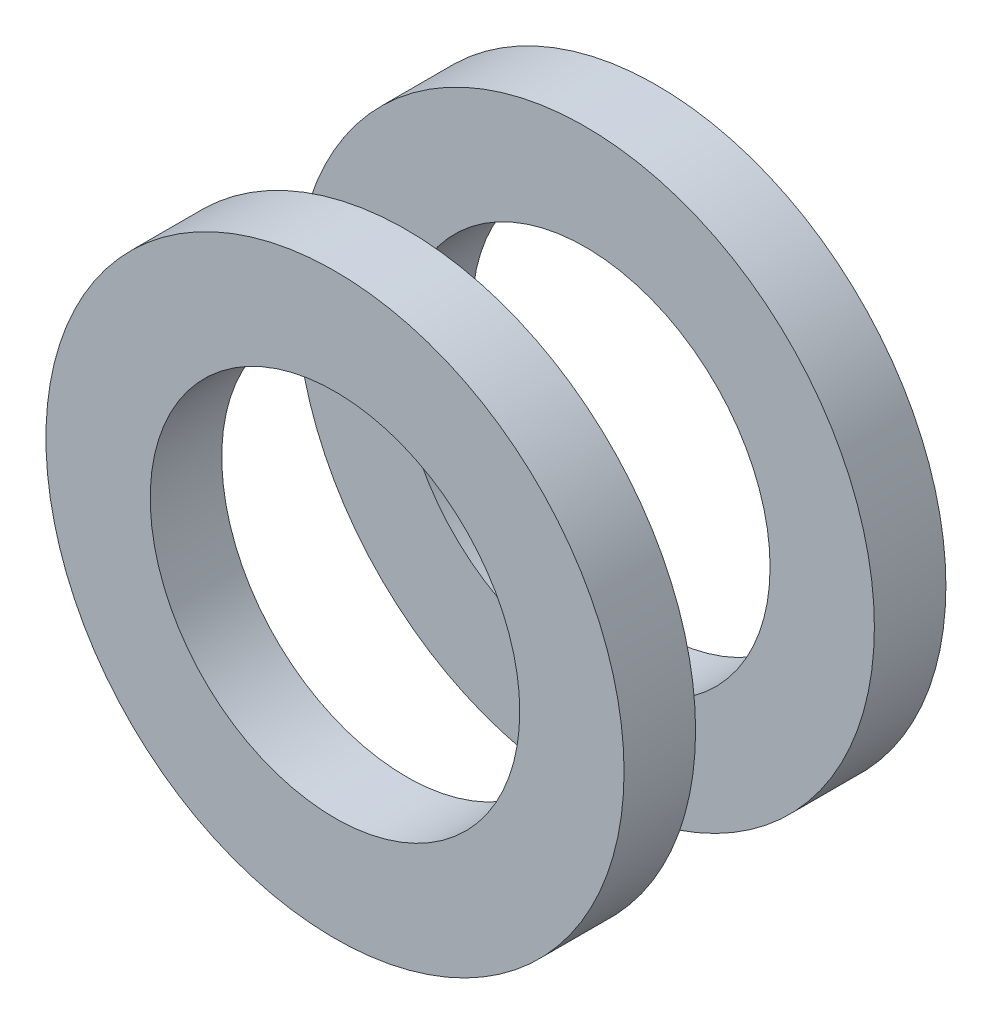
SolidWorks part; units mm, degrees
ref_plane "Спереди" through (0, 0, 0) normal (0, 0, 1) x (1, 0, 0)
ref_plane "Сверху" through (0, 0, 0) normal (0, 1, 0) x (1, 0, 0)
ref_plane "Справа" through (0, 0, 0) normal (1, 0, 0) x (0, 0, -1)
sketch "Эскиз1" plane through (0, 0, 0) normal (0, 0, 1) x (1, 0, 0)
  circle A0 centre (0, 0) radius 48.5
  circle A1 centre (0, 0) radius 31
extrude "Rear_endturn" add sketch "Эскиз1" along normal blind 12 from offset 27 separate body
sketch "Эскиз2" plane through (0, 0, 0) normal (0, 0, 1) x (1, 0, 0)
  circle A0 centre (0, 0) radius 48.5
  circle A1 centre (0, 0) radius 31
extrude "Front_endturn" add sketch "Эскиз2" along normal blind 12 from offset 15 separate body
